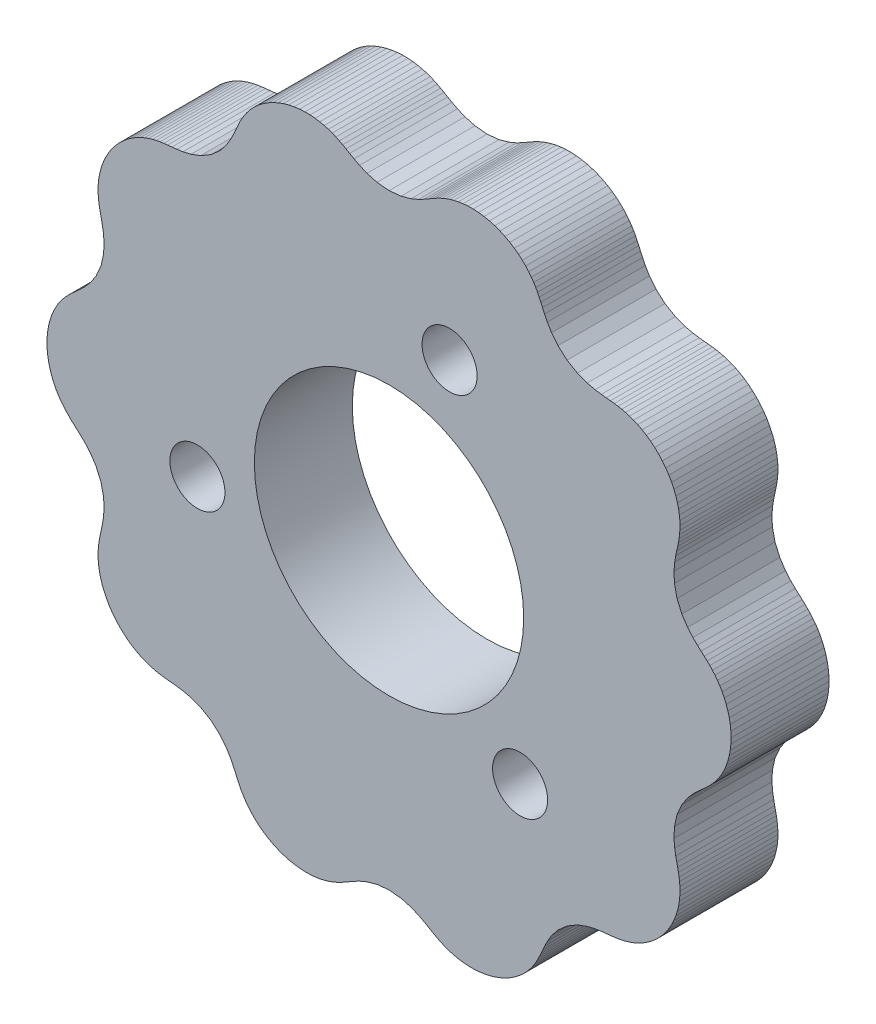
SolidWorks part; units mm, degrees
ref_plane "Front Plane" through (0, 0, 0) normal (0, 0, 1) x (1, 0, 0)
ref_plane "Top Plane" through (0, 0, 0) normal (0, 1, 0) x (1, 0, 0)
ref_plane "Right Plane" through (0, 0, 0) normal (1, 0, 0) x (0, 0, -1)
sketch "Model" plane through (0, 0, 0) normal (0, 0, 1) x (1, 0, 0)
  line L0 (20.955, 0) -> (20.9416, 0.365) construction
  line L1 (20.9416, 0.365) -> (20.9019, 0.7253) construction
  line L2 (20.9019, 0.7253) -> (20.8371, 1.0767) construction
  line L3 (20.8371, 1.0767) -> (20.749, 1.4151) construction
  line L4 (20.749, 1.4151) -> (20.6403, 1.7368) construction
  line L5 (20.6403, 1.7368) -> (20.514, 2.0391) construction
  line L6 (20.514, 2.0391) -> (20.3735, 2.32) construction
  line L7 (20.3735, 2.32) -> (20.2221, 2.5783) construction
  line L8 (20.2221, 2.5783) -> (20.0631, 2.8139) construction
  line L9 (20.0631, 2.8139) -> (19.8992, 3.0281) construction
  line L10 (19.8992, 3.0281) -> (19.7321, 3.2232) construction
  line L11 (19.7321, 3.2232) -> (19.5618, 3.4033) construction
  line L12 (19.5618, 3.4033) -> (19.3864, 3.5744) construction
  line L13 (19.3864, 3.5744) -> (19.2007, 3.7451) construction
  line L14 (19.2007, 3.7451) -> (18.9953, 3.9287) construction
  line L15 (18.9953, 3.9287) -> (18.7567, 4.1455) construction
  line L16 (18.7567, 4.1455) -> (18.4694, 4.4274) construction
  line L17 (18.4694, 4.4274) -> (18.1274, 4.8212) construction
  line L18 (18.1274, 4.8212) -> (17.7602, 5.3749) construction
  line L19 (17.7602, 5.3749) -> (17.4515, 6.083) construction
  line L20 (17.4515, 6.083) -> (17.285, 6.8373) construction
  line L21 (17.285, 6.8373) -> (17.2567, 7.5011) construction
  line L22 (17.2567, 7.5011) -> (17.3019, 8.0207) construction
  line L23 (17.3019, 8.0207) -> (17.3686, 8.4177) construction
  line L24 (17.3686, 8.4177) -> (17.4342, 8.7332) construction
  line L25 (17.4342, 8.7332) -> (17.4925, 9.0025) construction
  line L26 (17.4925, 9.0025) -> (17.5424, 9.2498) construction
  line L27 (17.5424, 9.2498) -> (17.5837, 9.4913) construction
  line L28 (17.5837, 9.4913) -> (17.6156, 9.7371) construction
  line L29 (17.6156, 9.7371) -> (17.6361, 9.9932) construction
  line L30 (17.6361, 9.9932) -> (17.6428, 10.2628) construction
  line L31 (17.6428, 10.2628) -> (17.6329, 10.5469) construction
  line L32 (17.6329, 10.5469) -> (17.6036, 10.8448) construction
  line L33 (17.6036, 10.8448) -> (17.5522, 11.1546) construction
  line L34 (17.5522, 11.1546) -> (17.4767, 11.4734) construction
  line L35 (17.4767, 11.4734) -> (17.3755, 11.7977) construction
  line L36 (17.3755, 11.7977) -> (17.2479, 12.1231) construction
  line L37 (17.2479, 12.1231) -> (17.0938, 12.4455) construction
  line L38 (17.0938, 12.4455) -> (16.9141, 12.7604) construction
  line L39 (16.9141, 12.7604) -> (16.7104, 13.0635) construction
  line L40 (16.7104, 13.0635) -> (16.4851, 13.3509) construction
  line L41 (16.4851, 13.3509) -> (16.2411, 13.6191) construction
  line L42 (16.2411, 13.6191) -> (15.9821, 13.8653) construction
  line L43 (15.9821, 13.8653) -> (15.712, 14.0873) construction
  line L44 (15.712, 14.0873) -> (15.4349, 14.2837) construction
  line L45 (15.4349, 14.2837) -> (15.1551, 14.454) construction
  line L46 (15.1551, 14.454) -> (14.8763, 14.5986) construction
  line L47 (14.8763, 14.5986) -> (14.602, 14.7186) construction
  line L48 (14.602, 14.7186) -> (14.3349, 14.8158) construction
  line L49 (14.3349, 14.8158) -> (14.0764, 14.8927) construction
  line L50 (14.0764, 14.8927) -> (13.8265, 14.9523) construction
  line L51 (13.8265, 14.9523) -> (13.5829, 14.998) construction
  line L52 (13.5829, 14.998) -> (13.3405, 15.0333) construction
  line L53 (13.3405, 15.0333) -> (13.0898, 15.0622) construction
  line L54 (13.0898, 15.0622) -> (12.8157, 15.0901) construction
  line L55 (12.8157, 15.0901) -> (12.4953, 15.1252) construction
  line L56 (12.4953, 15.1252) -> (12.0972, 15.1844) construction
  line L57 (12.0972, 15.1844) -> (11.589, 15.302) construction
  line L58 (11.589, 15.302) -> (10.9665, 15.534) construction
  line L59 (10.9665, 15.534) -> (10.3006, 15.9255) construction
  line L60 (10.3006, 15.9255) -> (9.7225, 16.4379) construction
  line L61 (9.7225, 16.4379) -> (9.3094, 16.9582) construction
  line L62 (9.3094, 16.9582) -> (9.0405, 17.4052) construction
  line L63 (9.0405, 17.4052) -> (8.8612, 17.7655) construction
  line L64 (8.8612, 17.7655) -> (8.7288, 18.0594) construction
  line L65 (8.7288, 18.0594) -> (8.6176, 18.3115) construction
  line L66 (8.6176, 18.3115) -> (8.5126, 18.5409) construction
  line L67 (8.5126, 18.5409) -> (8.4041, 18.7606) construction
  line L68 (8.4041, 18.7606) -> (8.2854, 18.9781) construction
  line L69 (8.2854, 18.9781) -> (8.1515, 19.1974) construction
  line L70 (8.1515, 19.1974) -> (7.9985, 19.4194) construction
  line L71 (7.9985, 19.4194) -> (7.8235, 19.6434) construction
  line L72 (7.8235, 19.6434) -> (7.6246, 19.8672) construction
  line L73 (7.6246, 19.8672) -> (7.401, 20.0877) construction
  line L74 (7.401, 20.0877) -> (7.1525, 20.3012) construction
  line L75 (7.1525, 20.3012) -> (6.8801, 20.5041) construction
  line L76 (6.8801, 20.5041) -> (6.5855, 20.6924) construction
  line L77 (6.5855, 20.6924) -> (6.2713, 20.8626) construction
  line L78 (6.2713, 20.8626) -> (5.9409, 21.0117) construction
  line L79 (5.9409, 21.0117) -> (5.5979, 21.1372) construction
  line L80 (5.5979, 21.1372) -> (5.2467, 21.2373) construction
  line L81 (5.2467, 21.2373) -> (4.8917, 21.3109) construction
  line L82 (4.8917, 21.3109) -> (4.5374, 21.3578) construction
  line L83 (4.5374, 21.3578) -> (4.1885, 21.3786) construction
  line L84 (4.1885, 21.3786) -> (3.8489, 21.3747) construction
  line L85 (3.8489, 21.3747) -> (3.5223, 21.348) construction
  line L86 (3.5223, 21.348) -> (3.2118, 21.3011) construction
  line L87 (3.2118, 21.3011) -> (2.9193, 21.2369) construction
  line L88 (2.9193, 21.2369) -> (2.6461, 21.1585) construction
  line L89 (2.6461, 21.1585) -> (2.3918, 21.0688) construction
  line L90 (2.3918, 21.0688) -> (2.1545, 20.9702) construction
  line L91 (2.1545, 20.9702) -> (1.9307, 20.8639) construction
  line L92 (1.9307, 20.8639) -> (1.7138, 20.75) construction
  line L93 (1.7138, 20.75) -> (1.4939, 20.6261) construction
  line L94 (1.4939, 20.6261) -> (1.2559, 20.4875) construction
  line L95 (1.2559, 20.4875) -> (0.976, 20.3276) construction
  line L96 (0.976, 20.3276) -> (0.6191, 20.1415) construction
  line L97 (0.6191, 20.1415) -> (0.1389, 19.9379) construction
  line L98 (0.1389, 19.9379) -> (-0.5012, 19.7597) construction
  line L99 (-0.5012, 19.7597) -> (-1.27, 19.685) construction
  line L100 (-1.27, 19.685) -> (-2.0388, 19.7597) construction
  line L101 (-2.0388, 19.7597) -> (-2.6789, 19.9379) construction
  line L102 (-2.6789, 19.9379) -> (-3.1591, 20.1415) construction
  line L103 (-3.1591, 20.1415) -> (-3.516, 20.3276) construction
  line L104 (-3.516, 20.3276) -> (-3.7959, 20.4875) construction
  line L105 (-3.7959, 20.4875) -> (-4.0339, 20.6261) construction
  line L106 (-4.0339, 20.6261) -> (-4.2538, 20.75) construction
  line L107 (-4.2538, 20.75) -> (-4.4707, 20.8639) construction
  line L108 (-4.4707, 20.8639) -> (-4.6945, 20.9702) construction
  line L109 (-4.6945, 20.9702) -> (-4.9318, 21.0688) construction
  line L110 (-4.9318, 21.0688) -> (-5.1861, 21.1585) construction
  line L111 (-5.1861, 21.1585) -> (-5.4593, 21.2369) construction
  line L112 (-5.4593, 21.2369) -> (-5.7518, 21.3011) construction
  line L113 (-5.7518, 21.3011) -> (-6.0623, 21.348) construction
  line L114 (-6.0623, 21.348) -> (-6.3889, 21.3747) construction
  line L115 (-6.3889, 21.3747) -> (-6.7285, 21.3786) construction
  line L116 (-6.7285, 21.3786) -> (-7.0774, 21.3578) construction
  line L117 (-7.0774, 21.3578) -> (-7.4317, 21.3109) construction
  line L118 (-7.4317, 21.3109) -> (-7.7867, 21.2373) construction
  line L119 (-7.7867, 21.2373) -> (-8.1379, 21.1372) construction
  line L120 (-8.1379, 21.1372) -> (-8.4809, 21.0117) construction
  line L121 (-8.4809, 21.0117) -> (-8.8113, 20.8626) construction
  line L122 (-8.8113, 20.8626) -> (-9.1255, 20.6924) construction
  line L123 (-9.1255, 20.6924) -> (-9.4201, 20.5041) construction
  line L124 (-9.4201, 20.5041) -> (-9.6925, 20.3012) construction
  line L125 (-9.6925, 20.3012) -> (-9.941, 20.0877) construction
  line L126 (-9.941, 20.0877) -> (-10.1646, 19.8672) construction
  line L127 (-10.1646, 19.8672) -> (-10.3635, 19.6434) construction
  line L128 (-10.3635, 19.6434) -> (-10.5385, 19.4194) construction
  line L129 (-10.5385, 19.4194) -> (-10.6915, 19.1974) construction
  line L130 (-10.6915, 19.1974) -> (-10.8254, 18.9781) construction
  line L131 (-10.8254, 18.9781) -> (-10.9441, 18.7606) construction
  line L132 (-10.9441, 18.7606) -> (-11.0526, 18.5409) construction
  line L133 (-11.0526, 18.5409) -> (-11.1576, 18.3115) construction
  line L134 (-11.1576, 18.3115) -> (-11.2688, 18.0594) construction
  line L135 (-11.2688, 18.0594) -> (-11.4012, 17.7655) construction
  line L136 (-11.4012, 17.7655) -> (-11.5805, 17.4052) construction
  line L137 (-11.5805, 17.4052) -> (-11.8494, 16.9582) construction
  line L138 (-11.8494, 16.9582) -> (-12.2625, 16.4379) construction
  line L139 (-12.2625, 16.4379) -> (-12.8406, 15.9255) construction
  line L140 (-12.8406, 15.9255) -> (-13.5065, 15.534) construction
  line L141 (-13.5065, 15.534) -> (-14.129, 15.302) construction
  line L142 (-14.129, 15.302) -> (-14.6372, 15.1844) construction
  line L143 (-14.6372, 15.1844) -> (-15.0353, 15.1252) construction
  line L144 (-15.0353, 15.1252) -> (-15.3557, 15.0901) construction
  line L145 (-15.3557, 15.0901) -> (-15.6298, 15.0622) construction
  line L146 (-15.6298, 15.0622) -> (-15.8805, 15.0333) construction
  line L147 (-15.8805, 15.0333) -> (-16.1229, 14.998) construction
  line L148 (-16.1229, 14.998) -> (-16.3665, 14.9523) construction
  line L149 (-16.3665, 14.9523) -> (-16.6164, 14.8927) construction
  line L150 (-16.6164, 14.8927) -> (-16.8749, 14.8158) construction
  line L151 (-16.8749, 14.8158) -> (-17.142, 14.7186) construction
  line L152 (-17.142, 14.7186) -> (-17.4163, 14.5986) construction
  line L153 (-17.4163, 14.5986) -> (-17.6951, 14.454) construction
  line L154 (-17.6951, 14.454) -> (-17.9749, 14.2837) construction
  line L155 (-17.9749, 14.2837) -> (-18.252, 14.0873) construction
  line L156 (-18.252, 14.0873) -> (-18.5221, 13.8653) construction
  line L157 (-18.5221, 13.8653) -> (-18.7811, 13.6191) construction
  line L158 (-18.7811, 13.6191) -> (-19.0251, 13.3509) construction
  line L159 (-19.0251, 13.3509) -> (-19.2504, 13.0635) construction
  line L160 (-19.2504, 13.0635) -> (-19.4541, 12.7604) construction
  line L161 (-19.4541, 12.7604) -> (-19.6338, 12.4455) construction
  line L162 (-19.6338, 12.4455) -> (-19.7879, 12.1231) construction
  line L163 (-19.7879, 12.1231) -> (-19.9155, 11.7977) construction
  line L164 (-19.9155, 11.7977) -> (-20.0167, 11.4734) construction
  line L165 (-20.0167, 11.4734) -> (-20.0922, 11.1546) construction
  line L166 (-20.0922, 11.1546) -> (-20.1436, 10.8448) construction
  line L167 (-20.1436, 10.8448) -> (-20.1729, 10.5469) construction
  line L168 (-20.1729, 10.5469) -> (-20.1828, 10.2628) construction
  line L169 (-20.1828, 10.2628) -> (-20.1761, 9.9932) construction
  line L170 (-20.1761, 9.9932) -> (-20.1556, 9.7371) construction
  line L171 (-20.1556, 9.7371) -> (-20.1237, 9.4913) construction
  line L172 (-20.1237, 9.4913) -> (-20.0824, 9.2498) construction
  line L173 (-20.0824, 9.2498) -> (-20.0325, 9.0025) construction
  line L174 (-20.0325, 9.0025) -> (-19.9742, 8.7332) construction
  line L175 (-19.9742, 8.7332) -> (-19.9086, 8.4177) construction
  line L176 (-19.9086, 8.4177) -> (-19.8419, 8.0207) construction
  line L177 (-19.8419, 8.0207) -> (-19.7967, 7.5011) construction
  line L178 (-19.7967, 7.5011) -> (-19.825, 6.8373) construction
  line L179 (-19.825, 6.8373) -> (-19.9915, 6.083) construction
  line L180 (-19.9915, 6.083) -> (-20.3002, 5.3749) construction
  line L181 (-20.3002, 5.3749) -> (-20.6674, 4.8212) construction
  line L182 (-20.6674, 4.8212) -> (-21.0094, 4.4274) construction
  line L183 (-21.0094, 4.4274) -> (-21.2967, 4.1455) construction
  line L184 (-21.2967, 4.1455) -> (-21.5353, 3.9287) construction
  line L185 (-21.5353, 3.9287) -> (-21.7407, 3.7451) construction
  line L186 (-21.7407, 3.7451) -> (-21.9264, 3.5744) construction
  line L187 (-21.9264, 3.5744) -> (-22.1018, 3.4033) construction
  line L188 (-22.1018, 3.4033) -> (-22.2721, 3.2232) construction
  line L189 (-22.2721, 3.2232) -> (-22.4392, 3.0281) construction
  line L190 (-22.4392, 3.0281) -> (-22.6031, 2.8139) construction
  line L191 (-22.6031, 2.8139) -> (-22.7621, 2.5783) construction
  line L192 (-22.7621, 2.5783) -> (-22.9135, 2.32) construction
  line L193 (-22.9135, 2.32) -> (-23.054, 2.0391) construction
  line L194 (-23.054, 2.0391) -> (-23.1803, 1.7368) construction
  line L195 (-23.1803, 1.7368) -> (-23.289, 1.4151) construction
  line L196 (-23.289, 1.4151) -> (-23.3771, 1.0767) construction
  line L197 (-23.3771, 1.0767) -> (-23.4419, 0.7253) construction
  line L198 (-23.4419, 0.7253) -> (-23.4816, 0.365) construction
  line L199 (-23.4816, 0.365) -> (-23.495, 0) construction
  line L200 (-23.495, 0) -> (-23.4816, -0.365) construction
  line L201 (-23.4816, -0.365) -> (-23.4419, -0.7253) construction
  line L202 (-23.4419, -0.7253) -> (-23.3771, -1.0767) construction
  line L203 (-23.3771, -1.0767) -> (-23.289, -1.4151) construction
  line L204 (-23.289, -1.4151) -> (-23.1803, -1.7368) construction
  line L205 (-23.1803, -1.7368) -> (-23.054, -2.0391) construction
  line L206 (-23.054, -2.0391) -> (-22.9135, -2.32) construction
  line L207 (-22.9135, -2.32) -> (-22.7621, -2.5783) construction
  line L208 (-22.7621, -2.5783) -> (-22.6031, -2.8139) construction
  line L209 (-22.6031, -2.8139) -> (-22.4392, -3.0281) construction
  line L210 (-22.4392, -3.0281) -> (-22.2721, -3.2232) construction
  line L211 (-22.2721, -3.2232) -> (-22.1018, -3.4033) construction
  line L212 (-22.1018, -3.4033) -> (-21.9264, -3.5744) construction
  line L213 (-21.9264, -3.5744) -> (-21.7407, -3.7451) construction
  line L214 (-21.7407, -3.7451) -> (-21.5353, -3.9287) construction
  line L215 (-21.5353, -3.9287) -> (-21.2967, -4.1455) construction
  line L216 (-21.2967, -4.1455) -> (-21.0094, -4.4274) construction
  line L217 (-21.0094, -4.4274) -> (-20.6674, -4.8212) construction
  line L218 (-20.6674, -4.8212) -> (-20.3002, -5.3749) construction
  line L219 (-20.3002, -5.3749) -> (-19.9915, -6.083) construction
  line L220 (-19.9915, -6.083) -> (-19.825, -6.8373) construction
  line L221 (-19.825, -6.8373) -> (-19.7967, -7.5011) construction
  line L222 (-19.7967, -7.5011) -> (-19.8419, -8.0207) construction
  line L223 (-19.8419, -8.0207) -> (-19.9086, -8.4177) construction
  line L224 (-19.9086, -8.4177) -> (-19.9742, -8.7332) construction
  line L225 (-19.9742, -8.7332) -> (-20.0325, -9.0025) construction
  line L226 (-20.0325, -9.0025) -> (-20.0824, -9.2498) construction
  line L227 (-20.0824, -9.2498) -> (-20.1237, -9.4913) construction
  line L228 (-20.1237, -9.4913) -> (-20.1556, -9.7371) construction
  line L229 (-20.1556, -9.7371) -> (-20.1761, -9.9932) construction
  line L230 (-20.1761, -9.9932) -> (-20.1828, -10.2628) construction
  line L231 (-20.1828, -10.2628) -> (-20.1729, -10.5469) construction
  line L232 (-20.1729, -10.5469) -> (-20.1436, -10.8448) construction
  line L233 (-20.1436, -10.8448) -> (-20.0922, -11.1546) construction
  line L234 (-20.0922, -11.1546) -> (-20.0167, -11.4734) construction
  line L235 (-20.0167, -11.4734) -> (-19.9155, -11.7977) construction
  line L236 (-19.9155, -11.7977) -> (-19.7879, -12.1231) construction
  line L237 (-19.7879, -12.1231) -> (-19.6338, -12.4455) construction
  line L238 (-19.6338, -12.4455) -> (-19.4541, -12.7604) construction
  line L239 (-19.4541, -12.7604) -> (-19.2504, -13.0635) construction
  line L240 (-19.2504, -13.0635) -> (-19.0251, -13.3509) construction
  line L241 (-19.0251, -13.3509) -> (-18.7811, -13.6191) construction
  line L242 (-18.7811, -13.6191) -> (-18.5221, -13.8653) construction
  line L243 (-18.5221, -13.8653) -> (-18.252, -14.0873) construction
  line L244 (-18.252, -14.0873) -> (-17.9749, -14.2837) construction
  line L245 (-17.9749, -14.2837) -> (-17.6951, -14.454) construction
  line L246 (-17.6951, -14.454) -> (-17.4163, -14.5986) construction
  line L247 (-17.4163, -14.5986) -> (-17.142, -14.7186) construction
  line L248 (-17.142, -14.7186) -> (-16.8749, -14.8158) construction
  line L249 (-16.8749, -14.8158) -> (-16.6164, -14.8927) construction
  line L250 (-16.6164, -14.8927) -> (-16.3665, -14.9523) construction
  line L251 (-16.3665, -14.9523) -> (-16.1229, -14.998) construction
  line L252 (-16.1229, -14.998) -> (-15.8805, -15.0333) construction
  line L253 (-15.8805, -15.0333) -> (-15.6298, -15.0622) construction
  line L254 (-15.6298, -15.0622) -> (-15.3557, -15.0901) construction
  line L255 (-15.3557, -15.0901) -> (-15.0353, -15.1252) construction
  line L256 (-15.0353, -15.1252) -> (-14.6372, -15.1844) construction
  line L257 (-14.6372, -15.1844) -> (-14.129, -15.302) construction
  line L258 (-14.129, -15.302) -> (-13.5065, -15.534) construction
  line L259 (-13.5065, -15.534) -> (-12.8406, -15.9255) construction
  line L260 (-12.8406, -15.9255) -> (-12.2625, -16.4379) construction
  line L261 (-12.2625, -16.4379) -> (-11.8494, -16.9582) construction
  line L262 (-11.8494, -16.9582) -> (-11.5805, -17.4052) construction
  line L263 (-11.5805, -17.4052) -> (-11.4012, -17.7655) construction
  line L264 (-11.4012, -17.7655) -> (-11.2688, -18.0594) construction
  line L265 (-11.2688, -18.0594) -> (-11.1576, -18.3115) construction
  line L266 (-11.1576, -18.3115) -> (-11.0526, -18.5409) construction
  line L267 (-11.0526, -18.5409) -> (-10.9441, -18.7606) construction
  line L268 (-10.9441, -18.7606) -> (-10.8254, -18.9781) construction
  line L269 (-10.8254, -18.9781) -> (-10.6915, -19.1974) construction
  line L270 (-10.6915, -19.1974) -> (-10.5385, -19.4194) construction
  line L271 (-10.5385, -19.4194) -> (-10.3635, -19.6434) construction
  line L272 (-10.3635, -19.6434) -> (-10.1646, -19.8672) construction
  line L273 (-10.1646, -19.8672) -> (-9.941, -20.0877) construction
  line L274 (-9.941, -20.0877) -> (-9.6925, -20.3012) construction
  line L275 (-9.6925, -20.3012) -> (-9.4201, -20.5041) construction
  line L276 (-9.4201, -20.5041) -> (-9.1255, -20.6924) construction
  line L277 (-9.1255, -20.6924) -> (-8.8113, -20.8626) construction
  line L278 (-8.8113, -20.8626) -> (-8.4809, -21.0117) construction
  line L279 (-8.4809, -21.0117) -> (-8.1379, -21.1372) construction
  line L280 (-8.1379, -21.1372) -> (-7.7867, -21.2373) construction
  line L281 (-7.7867, -21.2373) -> (-7.4317, -21.3109) construction
  line L282 (-7.4317, -21.3109) -> (-7.0774, -21.3578) construction
  line L283 (-7.0774, -21.3578) -> (-6.7285, -21.3786) construction
  line L284 (-6.7285, -21.3786) -> (-6.3889, -21.3747) construction
  line L285 (-6.3889, -21.3747) -> (-6.0623, -21.348) construction
  line L286 (-6.0623, -21.348) -> (-5.7518, -21.3011) construction
  line L287 (-5.7518, -21.3011) -> (-5.4593, -21.2369) construction
  line L288 (-5.4593, -21.2369) -> (-5.1861, -21.1585) construction
  line L289 (-5.1861, -21.1585) -> (-4.9318, -21.0688) construction
  line L290 (-4.9318, -21.0688) -> (-4.6945, -20.9702) construction
  line L291 (-4.6945, -20.9702) -> (-4.4707, -20.8639) construction
  line L292 (-4.4707, -20.8639) -> (-4.2538, -20.75) construction
  line L293 (-4.2538, -20.75) -> (-4.0339, -20.6261) construction
  line L294 (-4.0339, -20.6261) -> (-3.7959, -20.4875) construction
  line L295 (-3.7959, -20.4875) -> (-3.516, -20.3276) construction
  line L296 (-3.516, -20.3276) -> (-3.1591, -20.1415) construction
  line L297 (-3.1591, -20.1415) -> (-2.6789, -19.9379) construction
  line L298 (-2.6789, -19.9379) -> (-2.0388, -19.7597) construction
  line L299 (-2.0388, -19.7597) -> (-1.27, -19.685) construction
  line L300 (-1.27, -19.685) -> (-0.5012, -19.7597) construction
  line L301 (-0.5012, -19.7597) -> (0.1389, -19.9379) construction
  line L302 (0.1389, -19.9379) -> (0.6191, -20.1415) construction
  line L303 (0.6191, -20.1415) -> (0.976, -20.3276) construction
  line L304 (0.976, -20.3276) -> (1.2559, -20.4875) construction
  line L305 (1.2559, -20.4875) -> (1.4939, -20.6261) construction
  line L306 (1.4939, -20.6261) -> (1.7138, -20.75) construction
  line L307 (1.7138, -20.75) -> (1.9307, -20.8639) construction
  line L308 (1.9307, -20.8639) -> (2.1545, -20.9702) construction
  line L309 (2.1545, -20.9702) -> (2.3918, -21.0688) construction
  line L310 (2.3918, -21.0688) -> (2.6461, -21.1585) construction
  line L311 (2.6461, -21.1585) -> (2.9193, -21.2369) construction
  line L312 (2.9193, -21.2369) -> (3.2118, -21.3011) construction
  line L313 (3.2118, -21.3011) -> (3.5223, -21.348) construction
  line L314 (3.5223, -21.348) -> (3.8489, -21.3747) construction
  line L315 (3.8489, -21.3747) -> (4.1885, -21.3786) construction
  line L316 (4.1885, -21.3786) -> (4.5374, -21.3578) construction
  line L317 (4.5374, -21.3578) -> (4.8917, -21.3109) construction
  line L318 (4.8917, -21.3109) -> (5.2467, -21.2373) construction
  line L319 (5.2467, -21.2373) -> (5.5979, -21.1372) construction
  line L320 (5.5979, -21.1372) -> (5.9409, -21.0117) construction
  line L321 (5.9409, -21.0117) -> (6.2713, -20.8626) construction
  line L322 (6.2713, -20.8626) -> (6.5855, -20.6924) construction
  line L323 (6.5855, -20.6924) -> (6.8801, -20.5041) construction
  line L324 (6.8801, -20.5041) -> (7.1525, -20.3012) construction
  line L325 (7.1525, -20.3012) -> (7.401, -20.0877) construction
  line L326 (7.401, -20.0877) -> (7.6246, -19.8672) construction
  line L327 (7.6246, -19.8672) -> (7.8235, -19.6434) construction
  line L328 (7.8235, -19.6434) -> (7.9985, -19.4194) construction
  line L329 (7.9985, -19.4194) -> (8.1515, -19.1974) construction
  line L330 (8.1515, -19.1974) -> (8.2854, -18.9781) construction
  line L331 (8.2854, -18.9781) -> (8.4041, -18.7606) construction
  line L332 (8.4041, -18.7606) -> (8.5126, -18.5409) construction
  line L333 (8.5126, -18.5409) -> (8.6176, -18.3115) construction
  line L334 (8.6176, -18.3115) -> (8.7288, -18.0594) construction
  line L335 (8.7288, -18.0594) -> (8.8612, -17.7655) construction
  line L336 (8.8612, -17.7655) -> (9.0405, -17.4052) construction
  line L337 (9.0405, -17.4052) -> (9.3094, -16.9582) construction
  line L338 (9.3094, -16.9582) -> (9.7225, -16.4379) construction
  line L339 (9.7225, -16.4379) -> (10.3006, -15.9255) construction
  line L340 (10.3006, -15.9255) -> (10.9665, -15.534) construction
  line L341 (10.9665, -15.534) -> (11.589, -15.302) construction
  line L342 (11.589, -15.302) -> (12.0972, -15.1844) construction
  line L343 (12.0972, -15.1844) -> (12.4953, -15.1252) construction
  line L344 (12.4953, -15.1252) -> (12.8157, -15.0901) construction
  line L345 (12.8157, -15.0901) -> (13.0898, -15.0622) construction
  line L346 (13.0898, -15.0622) -> (13.3405, -15.0333) construction
  line L347 (13.3405, -15.0333) -> (13.5829, -14.998) construction
  line L348 (13.5829, -14.998) -> (13.8265, -14.9523) construction
  line L349 (13.8265, -14.9523) -> (14.0764, -14.8927) construction
  line L350 (14.0764, -14.8927) -> (14.3349, -14.8158) construction
  line L351 (14.3349, -14.8158) -> (14.602, -14.7186) construction
  line L352 (14.602, -14.7186) -> (14.8763, -14.5986) construction
  line L353 (14.8763, -14.5986) -> (15.1551, -14.454) construction
  line L354 (15.1551, -14.454) -> (15.4349, -14.2837) construction
  line L355 (15.4349, -14.2837) -> (15.712, -14.0873) construction
  line L356 (15.712, -14.0873) -> (15.9821, -13.8653) construction
  line L357 (15.9821, -13.8653) -> (16.2411, -13.6191) construction
  line L358 (16.2411, -13.6191) -> (16.4851, -13.3509) construction
  line L359 (16.4851, -13.3509) -> (16.7104, -13.0635) construction
  line L360 (16.7104, -13.0635) -> (16.9141, -12.7604) construction
  line L361 (16.9141, -12.7604) -> (17.0938, -12.4455) construction
  line L362 (17.0938, -12.4455) -> (17.2479, -12.1231) construction
  line L363 (17.2479, -12.1231) -> (17.3755, -11.7977) construction
  line L364 (17.3755, -11.7977) -> (17.4767, -11.4734) construction
  line L365 (17.4767, -11.4734) -> (17.5522, -11.1546) construction
  line L366 (17.5522, -11.1546) -> (17.6036, -10.8448) construction
  line L367 (17.6036, -10.8448) -> (17.6329, -10.5469) construction
  line L368 (17.6329, -10.5469) -> (17.6428, -10.2628) construction
  line L369 (17.6428, -10.2628) -> (17.6361, -9.9932) construction
  line L370 (17.6361, -9.9932) -> (17.6156, -9.7371) construction
  line L371 (17.6156, -9.7371) -> (17.5837, -9.4913) construction
  line L372 (17.5837, -9.4913) -> (17.5424, -9.2498) construction
  line L373 (17.5424, -9.2498) -> (17.4925, -9.0025) construction
  line L374 (17.4925, -9.0025) -> (17.4342, -8.7332) construction
  line L375 (17.4342, -8.7332) -> (17.3686, -8.4177) construction
  line L376 (17.3686, -8.4177) -> (17.3019, -8.0207) construction
  line L377 (17.3019, -8.0207) -> (17.2567, -7.5011) construction
  line L378 (17.2567, -7.5011) -> (17.285, -6.8373) construction
  line L379 (17.285, -6.8373) -> (17.4515, -6.083) construction
  line L380 (17.4515, -6.083) -> (17.7602, -5.3749) construction
  line L381 (17.7602, -5.3749) -> (18.1274, -4.8212) construction
  line L382 (18.1274, -4.8212) -> (18.4694, -4.4274) construction
  line L383 (18.4694, -4.4274) -> (18.7567, -4.1455) construction
  line L384 (18.7567, -4.1455) -> (18.9953, -3.9287) construction
  line L385 (18.9953, -3.9287) -> (19.2007, -3.7451) construction
  line L386 (19.2007, -3.7451) -> (19.3864, -3.5744) construction
  line L387 (19.3864, -3.5744) -> (19.5618, -3.4033) construction
  line L388 (19.5618, -3.4033) -> (19.7321, -3.2232) construction
  line L389 (19.7321, -3.2232) -> (19.8992, -3.0281) construction
  line L390 (19.8992, -3.0281) -> (20.0631, -2.8139) construction
  line L391 (20.0631, -2.8139) -> (20.2221, -2.5783) construction
  line L392 (20.2221, -2.5783) -> (20.3735, -2.32) construction
  line L393 (20.3735, -2.32) -> (20.514, -2.0391) construction
  line L394 (20.514, -2.0391) -> (20.6403, -1.7368) construction
  line L395 (20.6403, -1.7368) -> (20.749, -1.4151) construction
  line L396 (20.749, -1.4151) -> (20.8371, -1.0767) construction
  line L397 (20.8371, -1.0767) -> (20.9019, -0.7253) construction
  line L398 (20.9019, -0.7253) -> (20.9416, -0.365) construction
  line L399 (20.9416, -0.365) -> (20.955, 0) construction
  line L400 (20.9042, 0) -> (20.8909, 0.3612)
  line L401 (20.8909, 0.3612) -> (20.8516, 0.7179)
  line L402 (20.8516, 0.7179) -> (20.7875, 1.0657)
  line L403 (20.7875, 1.0657) -> (20.7003, 1.4005)
  line L404 (20.7003, 1.4005) -> (20.5928, 1.7189)
  line L405 (20.5928, 1.7189) -> (20.4678, 2.018)
  line L406 (20.4678, 2.018) -> (20.3288, 2.2958)
  line L407 (20.3288, 2.2958) -> (20.1791, 2.5512)
  line L408 (20.1791, 2.5512) -> (20.0218, 2.7843)
  line L409 (20.0218, 2.7843) -> (19.8597, 2.9961)
  line L410 (19.8597, 2.9961) -> (19.6943, 3.1892)
  line L411 (19.6943, 3.1892) -> (19.5256, 3.3677)
  line L412 (19.5256, 3.3677) -> (19.3515, 3.5375)
  line L413 (19.3515, 3.5375) -> (19.1666, 3.7075)
  line L414 (19.1666, 3.7075) -> (18.9613, 3.891)
  line L415 (18.9613, 3.891) -> (18.7218, 4.1085)
  line L416 (18.7218, 4.1085) -> (18.4324, 4.3925)
  line L417 (18.4324, 4.3925) -> (18.0869, 4.7904)
  line L418 (18.0869, 4.7904) -> (17.7154, 5.3505)
  line L419 (17.7154, 5.3505) -> (17.403, 6.0672)
  line L420 (17.403, 6.0672) -> (17.2345, 6.8307)
  line L421 (17.2345, 6.8307) -> (17.2058, 7.5022)
  line L422 (17.2058, 7.5022) -> (17.2515, 8.0271)
  line L423 (17.2515, 8.0271) -> (17.3187, 8.427)
  line L424 (17.3187, 8.427) -> (17.3845, 8.7438)
  line L425 (17.3845, 8.7438) -> (17.4427, 9.0129)
  line L426 (17.4427, 9.0129) -> (17.4924, 9.2591)
  line L427 (17.4924, 9.2591) -> (17.5335, 9.4989)
  line L428 (17.5335, 9.4989) -> (17.565, 9.7424)
  line L429 (17.565, 9.7424) -> (17.5854, 9.9958)
  line L430 (17.5854, 9.9958) -> (17.592, 10.2625)
  line L431 (17.592, 10.2625) -> (17.5822, 10.5435)
  line L432 (17.5822, 10.5435) -> (17.5532, 10.8381)
  line L433 (17.5532, 10.8381) -> (17.5024, 11.1446)
  line L434 (17.5024, 11.1446) -> (17.4277, 11.46)
  line L435 (17.4277, 11.46) -> (17.3276, 11.7808)
  line L436 (17.3276, 11.7808) -> (17.2013, 12.1029)
  line L437 (17.2013, 12.1029) -> (17.0488, 12.4219)
  line L438 (17.0488, 12.4219) -> (16.8709, 12.7336)
  line L439 (16.8709, 12.7336) -> (16.6693, 13.0336)
  line L440 (16.6693, 13.0336) -> (16.4462, 13.3181)
  line L441 (16.4462, 13.3181) -> (16.2048, 13.5836)
  line L442 (16.2048, 13.5836) -> (15.9485, 13.8272)
  line L443 (15.9485, 13.8272) -> (15.6812, 14.0469)
  line L444 (15.6812, 14.0469) -> (15.407, 14.2412)
  line L445 (15.407, 14.2412) -> (15.1301, 14.4097)
  line L446 (15.1301, 14.4097) -> (14.8544, 14.5527)
  line L447 (14.8544, 14.5527) -> (14.5831, 14.6714)
  line L448 (14.5831, 14.6714) -> (14.3189, 14.7675)
  line L449 (14.3189, 14.7675) -> (14.0632, 14.8436)
  line L450 (14.0632, 14.8436) -> (13.8159, 14.9026)
  line L451 (13.8159, 14.9026) -> (13.5746, 14.9479)
  line L452 (13.5746, 14.9479) -> (13.3339, 14.9829)
  line L453 (13.3339, 14.9829) -> (13.0843, 15.0117)
  line L454 (13.0843, 15.0117) -> (12.8104, 15.0395)
  line L455 (12.8104, 15.0395) -> (12.4888, 15.0748)
  line L456 (12.4888, 15.0748) -> (12.0877, 15.1344)
  line L457 (12.0877, 15.1344) -> (11.5743, 15.2533)
  line L458 (11.5743, 15.2533) -> (10.9446, 15.488)
  line L459 (10.9446, 15.488) -> (10.2706, 15.8842)
  line L460 (10.2706, 15.8842) -> (9.6855, 16.4028)
  line L461 (9.6855, 16.4028) -> (9.2676, 16.9292)
  line L462 (9.2676, 16.9292) -> (8.9959, 17.3807)
  line L463 (8.9959, 17.3807) -> (8.8152, 17.7438)
  line L464 (8.8152, 17.7438) -> (8.6824, 18.0387)
  line L465 (8.6824, 18.0387) -> (8.5713, 18.2906)
  line L466 (8.5713, 18.2906) -> (8.4667, 18.5191)
  line L467 (8.4667, 18.5191) -> (8.359, 18.7372)
  line L468 (8.359, 18.7372) -> (8.2414, 18.9527)
  line L469 (8.2414, 18.9527) -> (8.1089, 19.1697)
  line L470 (8.1089, 19.1697) -> (7.9575, 19.3894)
  line L471 (7.9575, 19.3894) -> (7.7845, 19.6109)
  line L472 (7.7845, 19.6109) -> (7.5878, 19.8322)
  line L473 (7.5878, 19.8322) -> (7.3665, 20.0503)
  line L474 (7.3665, 20.0503) -> (7.1207, 20.2616)
  line L475 (7.1207, 20.2616) -> (6.8512, 20.4622)
  line L476 (6.8512, 20.4622) -> (6.5597, 20.6486)
  line L477 (6.5597, 20.6486) -> (6.2488, 20.8171)
  line L478 (6.2488, 20.8171) -> (5.9217, 20.9647)
  line L479 (5.9217, 20.9647) -> (5.5822, 21.0889)
  line L480 (5.5822, 21.0889) -> (5.2345, 21.1879)
  line L481 (5.2345, 21.1879) -> (4.8832, 21.2608)
  line L482 (4.8832, 21.2608) -> (4.5326, 21.3072)
  line L483 (4.5326, 21.3072) -> (4.1872, 21.3278)
  line L484 (4.1872, 21.3278) -> (3.8512, 21.3239)
  line L485 (3.8512, 21.3239) -> (3.5282, 21.2975)
  line L486 (3.5282, 21.2975) -> (3.221, 21.2511)
  line L487 (3.221, 21.2511) -> (2.9318, 21.1876)
  line L488 (2.9318, 21.1876) -> (2.6616, 21.1101)
  line L489 (2.6616, 21.1101) -> (2.41, 21.0214)
  line L490 (2.41, 21.0214) -> (2.1752, 20.9237)
  line L491 (2.1752, 20.9237) -> (1.9534, 20.8185)
  line L492 (1.9534, 20.8185) -> (1.7381, 20.7054)
  line L493 (1.7381, 20.7054) -> (1.5192, 20.582)
  line L494 (1.5192, 20.582) -> (1.2813, 20.4435)
  line L495 (1.2813, 20.4435) -> (1.0004, 20.283)
  line L496 (1.0004, 20.283) -> (0.6408, 20.0955)
  line L497 (0.6408, 20.0955) -> (0.1557, 19.8899)
  line L498 (0.1557, 19.8899) -> (-0.4918, 19.7096)
  line L499 (-0.4918, 19.7096) -> (-1.27, 19.634)
  line L500 (-1.27, 19.634) -> (-2.0482, 19.7096)
  line L501 (-2.0482, 19.7096) -> (-2.6957, 19.8899)
  line L502 (-2.6957, 19.8899) -> (-3.1808, 20.0955)
  line L503 (-3.1808, 20.0955) -> (-3.5404, 20.283)
  line L504 (-3.5404, 20.283) -> (-3.8213, 20.4435)
  line L505 (-3.8213, 20.4435) -> (-4.0592, 20.582)
  line L506 (-4.0592, 20.582) -> (-4.2781, 20.7054)
  line L507 (-4.2781, 20.7054) -> (-4.4934, 20.8185)
  line L508 (-4.4934, 20.8185) -> (-4.7152, 20.9237)
  line L509 (-4.7152, 20.9237) -> (-4.95, 21.0214)
  line L510 (-4.95, 21.0214) -> (-5.2016, 21.1101)
  line L511 (-5.2016, 21.1101) -> (-5.4718, 21.1876)
  line L512 (-5.4718, 21.1876) -> (-5.761, 21.2511)
  line L513 (-5.761, 21.2511) -> (-6.0682, 21.2975)
  line L514 (-6.0682, 21.2975) -> (-6.3912, 21.3239)
  line L515 (-6.3912, 21.3239) -> (-6.7272, 21.3278)
  line L516 (-6.7272, 21.3278) -> (-7.0726, 21.3072)
  line L517 (-7.0726, 21.3072) -> (-7.4232, 21.2608)
  line L518 (-7.4232, 21.2608) -> (-7.7745, 21.1879)
  line L519 (-7.7745, 21.1879) -> (-8.1222, 21.0889)
  line L520 (-8.1222, 21.0889) -> (-8.4617, 20.9647)
  line L521 (-8.4617, 20.9647) -> (-8.7888, 20.8171)
  line L522 (-8.7888, 20.8171) -> (-9.0997, 20.6486)
  line L523 (-9.0997, 20.6486) -> (-9.3912, 20.4622)
  line L524 (-9.3912, 20.4622) -> (-9.6607, 20.2616)
  line L525 (-9.6607, 20.2616) -> (-9.9065, 20.0503)
  line L526 (-9.9065, 20.0503) -> (-10.1278, 19.8322)
  line L527 (-10.1278, 19.8322) -> (-10.3245, 19.6109)
  line L528 (-10.3245, 19.6109) -> (-10.4975, 19.3894)
  line L529 (-10.4975, 19.3894) -> (-10.6489, 19.1697)
  line L530 (-10.6489, 19.1697) -> (-10.7814, 18.9527)
  line L531 (-10.7814, 18.9527) -> (-10.899, 18.7372)
  line L532 (-10.899, 18.7372) -> (-11.0067, 18.5191)
  line L533 (-11.0067, 18.5191) -> (-11.1113, 18.2906)
  line L534 (-11.1113, 18.2906) -> (-11.2224, 18.0387)
  line L535 (-11.2224, 18.0387) -> (-11.3552, 17.7438)
  line L536 (-11.3552, 17.7438) -> (-11.5359, 17.3807)
  line L537 (-11.5359, 17.3807) -> (-11.8076, 16.9292)
  line L538 (-11.8076, 16.9292) -> (-12.2255, 16.4028)
  line L539 (-12.2255, 16.4028) -> (-12.8106, 15.8842)
  line L540 (-12.8106, 15.8842) -> (-13.4846, 15.488)
  line L541 (-13.4846, 15.488) -> (-14.1143, 15.2533)
  line L542 (-14.1143, 15.2533) -> (-14.6277, 15.1344)
  line L543 (-14.6277, 15.1344) -> (-15.0288, 15.0748)
  line L544 (-15.0288, 15.0748) -> (-15.3504, 15.0395)
  line L545 (-15.3504, 15.0395) -> (-15.6243, 15.0117)
  line L546 (-15.6243, 15.0117) -> (-15.8739, 14.9829)
  line L547 (-15.8739, 14.9829) -> (-16.1146, 14.9479)
  line L548 (-16.1146, 14.9479) -> (-16.3559, 14.9026)
  line L549 (-16.3559, 14.9026) -> (-16.6032, 14.8436)
  line L550 (-16.6032, 14.8436) -> (-16.8589, 14.7675)
  line L551 (-16.8589, 14.7675) -> (-17.1231, 14.6714)
  line L552 (-17.1231, 14.6714) -> (-17.3944, 14.5527)
  line L553 (-17.3944, 14.5527) -> (-17.6701, 14.4097)
  line L554 (-17.6701, 14.4097) -> (-17.947, 14.2412)
  line L555 (-17.947, 14.2412) -> (-18.2212, 14.0469)
  line L556 (-18.2212, 14.0469) -> (-18.4885, 13.8272)
  line L557 (-18.4885, 13.8272) -> (-18.7448, 13.5836)
  line L558 (-18.7448, 13.5836) -> (-18.9862, 13.3181)
  line L559 (-18.9862, 13.3181) -> (-19.2093, 13.0336)
  line L560 (-19.2093, 13.0336) -> (-19.4109, 12.7336)
  line L561 (-19.4109, 12.7336) -> (-19.5888, 12.4219)
  line L562 (-19.5888, 12.4219) -> (-19.7413, 12.1029)
  line L563 (-19.7413, 12.1029) -> (-19.8676, 11.7808)
  line L564 (-19.8676, 11.7808) -> (-19.9677, 11.46)
  line L565 (-19.9677, 11.46) -> (-20.0424, 11.1446)
  line L566 (-20.0424, 11.1446) -> (-20.0932, 10.8381)
  line L567 (-20.0932, 10.8381) -> (-20.1222, 10.5435)
  line L568 (-20.1222, 10.5435) -> (-20.132, 10.2625)
  line L569 (-20.132, 10.2625) -> (-20.1254, 9.9958)
  line L570 (-20.1254, 9.9958) -> (-20.105, 9.7424)
  line L571 (-20.105, 9.7424) -> (-20.0735, 9.4989)
  line L572 (-20.0735, 9.4989) -> (-20.0324, 9.2591)
  line L573 (-20.0324, 9.2591) -> (-19.9827, 9.0129)
  line L574 (-19.9827, 9.0129) -> (-19.9245, 8.7438)
  line L575 (-19.9245, 8.7438) -> (-19.8587, 8.427)
  line L576 (-19.8587, 8.427) -> (-19.7915, 8.0271)
  line L577 (-19.7915, 8.0271) -> (-19.7458, 7.5022)
  line L578 (-19.7458, 7.5022) -> (-19.7745, 6.8307)
  line L579 (-19.7745, 6.8307) -> (-19.943, 6.0672)
  line L580 (-19.943, 6.0672) -> (-20.2554, 5.3505)
  line L581 (-20.2554, 5.3505) -> (-20.6269, 4.7904)
  line L582 (-20.6269, 4.7904) -> (-20.9724, 4.3925)
  line L583 (-20.9724, 4.3925) -> (-21.2618, 4.1085)
  line L584 (-21.2618, 4.1085) -> (-21.5013, 3.891)
  line L585 (-21.5013, 3.891) -> (-21.7066, 3.7075)
  line L586 (-21.7066, 3.7075) -> (-21.8915, 3.5375)
  line L587 (-21.8915, 3.5375) -> (-22.0656, 3.3677)
  line L588 (-22.0656, 3.3677) -> (-22.2343, 3.1892)
  line L589 (-22.2343, 3.1892) -> (-22.3997, 2.9961)
  line L590 (-22.3997, 2.9961) -> (-22.5618, 2.7843)
  line L591 (-22.5618, 2.7843) -> (-22.7191, 2.5512)
  line L592 (-22.7191, 2.5512) -> (-22.8688, 2.2958)
  line L593 (-22.8688, 2.2958) -> (-23.0078, 2.018)
  line L594 (-23.0078, 2.018) -> (-23.1328, 1.7189)
  line L595 (-23.1328, 1.7189) -> (-23.2403, 1.4005)
  line L596 (-23.2403, 1.4005) -> (-23.3275, 1.0657)
  line L597 (-23.3275, 1.0657) -> (-23.3916, 0.7179)
  line L598 (-23.3916, 0.7179) -> (-23.4309, 0.3612)
  line L599 (-23.4309, 0.3612) -> (-23.4442, 0)
  line L600 (-23.4442, 0) -> (-23.4309, -0.3612)
  line L601 (-23.4309, -0.3612) -> (-23.3916, -0.7179)
  line L602 (-23.3916, -0.7179) -> (-23.3275, -1.0657)
  line L603 (-23.3275, -1.0657) -> (-23.2403, -1.4005)
  line L604 (-23.2403, -1.4005) -> (-23.1328, -1.7189)
  line L605 (-23.1328, -1.7189) -> (-23.0078, -2.018)
  line L606 (-23.0078, -2.018) -> (-22.8688, -2.2958)
  line L607 (-22.8688, -2.2958) -> (-22.7191, -2.5512)
  line L608 (-22.7191, -2.5512) -> (-22.5618, -2.7843)
  line L609 (-22.5618, -2.7843) -> (-22.3997, -2.9961)
  line L610 (-22.3997, -2.9961) -> (-22.2343, -3.1892)
  line L611 (-22.2343, -3.1892) -> (-22.0656, -3.3677)
  line L612 (-22.0656, -3.3677) -> (-21.8915, -3.5375)
  line L613 (-21.8915, -3.5375) -> (-21.7066, -3.7075)
  line L614 (-21.7066, -3.7075) -> (-21.5013, -3.891)
  line L615 (-21.5013, -3.891) -> (-21.2618, -4.1085)
  line L616 (-21.2618, -4.1085) -> (-20.9724, -4.3925)
  line L617 (-20.9724, -4.3925) -> (-20.6269, -4.7904)
  line L618 (-20.6269, -4.7904) -> (-20.2554, -5.3505)
  line L619 (-20.2554, -5.3505) -> (-19.943, -6.0672)
  line L620 (-19.943, -6.0672) -> (-19.7745, -6.8307)
  line L621 (-19.7745, -6.8307) -> (-19.7458, -7.5022)
  line L622 (-19.7458, -7.5022) -> (-19.7915, -8.0271)
  line L623 (-19.7915, -8.0271) -> (-19.8587, -8.427)
  line L624 (-19.8587, -8.427) -> (-19.9245, -8.7438)
  line L625 (-19.9245, -8.7438) -> (-19.9827, -9.0129)
  line L626 (-19.9827, -9.0129) -> (-20.0324, -9.2591)
  line L627 (-20.0324, -9.2591) -> (-20.0735, -9.4989)
  line L628 (-20.0735, -9.4989) -> (-20.105, -9.7424)
  line L629 (-20.105, -9.7424) -> (-20.1254, -9.9958)
  line L630 (-20.1254, -9.9958) -> (-20.132, -10.2625)
  line L631 (-20.132, -10.2625) -> (-20.1222, -10.5435)
  line L632 (-20.1222, -10.5435) -> (-20.0932, -10.8381)
  line L633 (-20.0932, -10.8381) -> (-20.0424, -11.1446)
  line L634 (-20.0424, -11.1446) -> (-19.9677, -11.46)
  line L635 (-19.9677, -11.46) -> (-19.8676, -11.7808)
  line L636 (-19.8676, -11.7808) -> (-19.7413, -12.1029)
  line L637 (-19.7413, -12.1029) -> (-19.5888, -12.4219)
  line L638 (-19.5888, -12.4219) -> (-19.4109, -12.7336)
  line L639 (-19.4109, -12.7336) -> (-19.2093, -13.0336)
  line L640 (-19.2093, -13.0336) -> (-18.9862, -13.3181)
  line L641 (-18.9862, -13.3181) -> (-18.7448, -13.5836)
  line L642 (-18.7448, -13.5836) -> (-18.4885, -13.8272)
  line L643 (-18.4885, -13.8272) -> (-18.2212, -14.0469)
  line L644 (-18.2212, -14.0469) -> (-17.947, -14.2412)
  line L645 (-17.947, -14.2412) -> (-17.6701, -14.4097)
  line L646 (-17.6701, -14.4097) -> (-17.3944, -14.5527)
  line L647 (-17.3944, -14.5527) -> (-17.1231, -14.6714)
  line L648 (-17.1231, -14.6714) -> (-16.8589, -14.7675)
  line L649 (-16.8589, -14.7675) -> (-16.6032, -14.8436)
  line L650 (-16.6032, -14.8436) -> (-16.3559, -14.9026)
  line L651 (-16.3559, -14.9026) -> (-16.1146, -14.9479)
  line L652 (-16.1146, -14.9479) -> (-15.8739, -14.9829)
  line L653 (-15.8739, -14.9829) -> (-15.6243, -15.0117)
  line L654 (-15.6243, -15.0117) -> (-15.3504, -15.0395)
  line L655 (-15.3504, -15.0395) -> (-15.0288, -15.0748)
  line L656 (-15.0288, -15.0748) -> (-14.6277, -15.1344)
  line L657 (-14.6277, -15.1344) -> (-14.1143, -15.2533)
  line L658 (-14.1143, -15.2533) -> (-13.4846, -15.488)
  line L659 (-13.4846, -15.488) -> (-12.8106, -15.8842)
  line L660 (-12.8106, -15.8842) -> (-12.2255, -16.4028)
  line L661 (-12.2255, -16.4028) -> (-11.8076, -16.9292)
  line L662 (-11.8076, -16.9292) -> (-11.5359, -17.3807)
  line L663 (-11.5359, -17.3807) -> (-11.3552, -17.7438)
  line L664 (-11.3552, -17.7438) -> (-11.2224, -18.0387)
  line L665 (-11.2224, -18.0387) -> (-11.1113, -18.2906)
  line L666 (-11.1113, -18.2906) -> (-11.0067, -18.5191)
  line L667 (-11.0067, -18.5191) -> (-10.899, -18.7372)
  line L668 (-10.899, -18.7372) -> (-10.7814, -18.9527)
  line L669 (-10.7814, -18.9527) -> (-10.6489, -19.1697)
  line L670 (-10.6489, -19.1697) -> (-10.4975, -19.3894)
  line L671 (-10.4975, -19.3894) -> (-10.3245, -19.6109)
  line L672 (-10.3245, -19.6109) -> (-10.1278, -19.8322)
  line L673 (-10.1278, -19.8322) -> (-9.9065, -20.0503)
  line L674 (-9.9065, -20.0503) -> (-9.6607, -20.2616)
  line L675 (-9.6607, -20.2616) -> (-9.3912, -20.4622)
  line L676 (-9.3912, -20.4622) -> (-9.0997, -20.6486)
  line L677 (-9.0997, -20.6486) -> (-8.7888, -20.8171)
  line L678 (-8.7888, -20.8171) -> (-8.4617, -20.9647)
  line L679 (-8.4617, -20.9647) -> (-8.1222, -21.0889)
  line L680 (-8.1222, -21.0889) -> (-7.7745, -21.1879)
  line L681 (-7.7745, -21.1879) -> (-7.4232, -21.2608)
  line L682 (-7.4232, -21.2608) -> (-7.0726, -21.3072)
  line L683 (-7.0726, -21.3072) -> (-6.7272, -21.3278)
  line L684 (-6.7272, -21.3278) -> (-6.3912, -21.3239)
  line L685 (-6.3912, -21.3239) -> (-6.0682, -21.2975)
  line L686 (-6.0682, -21.2975) -> (-5.761, -21.2511)
  line L687 (-5.761, -21.2511) -> (-5.4718, -21.1876)
  line L688 (-5.4718, -21.1876) -> (-5.2016, -21.1101)
  line L689 (-5.2016, -21.1101) -> (-4.95, -21.0214)
  line L690 (-4.95, -21.0214) -> (-4.7152, -20.9237)
  line L691 (-4.7152, -20.9237) -> (-4.4934, -20.8185)
  line L692 (-4.4934, -20.8185) -> (-4.2781, -20.7054)
  line L693 (-4.2781, -20.7054) -> (-4.0592, -20.582)
  line L694 (-4.0592, -20.582) -> (-3.8213, -20.4435)
  line L695 (-3.8213, -20.4435) -> (-3.5404, -20.283)
  line L696 (-3.5404, -20.283) -> (-3.1808, -20.0955)
  line L697 (-3.1808, -20.0955) -> (-2.6957, -19.8899)
  line L698 (-2.6957, -19.8899) -> (-2.0482, -19.7096)
  line L699 (-2.0482, -19.7096) -> (-1.27, -19.634)
  line L700 (-1.27, -19.634) -> (-0.4918, -19.7096)
  line L701 (-0.4918, -19.7096) -> (0.1557, -19.8899)
  line L702 (0.1557, -19.8899) -> (0.6408, -20.0955)
  line L703 (0.6408, -20.0955) -> (1.0004, -20.283)
  line L704 (1.0004, -20.283) -> (1.2813, -20.4435)
  line L705 (1.2813, -20.4435) -> (1.5192, -20.582)
  line L706 (1.5192, -20.582) -> (1.7381, -20.7054)
  line L707 (1.7381, -20.7054) -> (1.9534, -20.8185)
  line L708 (1.9534, -20.8185) -> (2.1752, -20.9237)
  line L709 (2.1752, -20.9237) -> (2.41, -21.0214)
  line L710 (2.41, -21.0214) -> (2.6616, -21.1101)
  line L711 (2.6616, -21.1101) -> (2.9318, -21.1876)
  line L712 (2.9318, -21.1876) -> (3.221, -21.2511)
  line L713 (3.221, -21.2511) -> (3.5282, -21.2975)
  line L714 (3.5282, -21.2975) -> (3.8512, -21.3239)
  line L715 (3.8512, -21.3239) -> (4.1872, -21.3278)
  line L716 (4.1872, -21.3278) -> (4.5326, -21.3072)
  line L717 (4.5326, -21.3072) -> (4.8832, -21.2608)
  line L718 (4.8832, -21.2608) -> (5.2345, -21.1879)
  line L719 (5.2345, -21.1879) -> (5.5822, -21.0889)
  line L720 (5.5822, -21.0889) -> (5.9217, -20.9647)
  line L721 (5.9217, -20.9647) -> (6.2488, -20.8171)
  line L722 (6.2488, -20.8171) -> (6.5597, -20.6486)
  line L723 (6.5597, -20.6486) -> (6.8512, -20.4622)
  line L724 (6.8512, -20.4622) -> (7.1207, -20.2616)
  line L725 (7.1207, -20.2616) -> (7.3665, -20.0503)
  line L726 (7.3665, -20.0503) -> (7.5878, -19.8322)
  line L727 (7.5878, -19.8322) -> (7.7845, -19.6109)
  line L728 (7.7845, -19.6109) -> (7.9575, -19.3894)
  line L729 (7.9575, -19.3894) -> (8.1089, -19.1697)
  line L730 (8.1089, -19.1697) -> (8.2414, -18.9527)
  line L731 (8.2414, -18.9527) -> (8.359, -18.7372)
  line L732 (8.359, -18.7372) -> (8.4667, -18.5191)
  line L733 (8.4667, -18.5191) -> (8.5713, -18.2906)
  line L734 (8.5713, -18.2906) -> (8.6824, -18.0387)
  line L735 (8.6824, -18.0387) -> (8.8152, -17.7438)
  line L736 (8.8152, -17.7438) -> (8.9959, -17.3807)
  line L737 (8.9959, -17.3807) -> (9.2676, -16.9292)
  line L738 (9.2676, -16.9292) -> (9.6855, -16.4028)
  line L739 (9.6855, -16.4028) -> (10.2706, -15.8842)
  line L740 (10.2706, -15.8842) -> (10.9446, -15.488)
  line L741 (10.9446, -15.488) -> (11.5743, -15.2533)
  line L742 (11.5743, -15.2533) -> (12.0877, -15.1344)
  line L743 (12.0877, -15.1344) -> (12.4888, -15.0748)
  line L744 (12.4888, -15.0748) -> (12.8104, -15.0395)
  line L745 (12.8104, -15.0395) -> (13.0843, -15.0117)
  line L746 (13.0843, -15.0117) -> (13.3339, -14.9829)
  line L747 (13.3339, -14.9829) -> (13.5746, -14.9479)
  line L748 (13.5746, -14.9479) -> (13.8159, -14.9026)
  line L749 (13.8159, -14.9026) -> (14.0632, -14.8436)
  line L750 (14.0632, -14.8436) -> (14.3189, -14.7675)
  line L751 (14.3189, -14.7675) -> (14.5831, -14.6714)
  line L752 (14.5831, -14.6714) -> (14.8544, -14.5527)
  line L753 (14.8544, -14.5527) -> (15.1301, -14.4097)
  line L754 (15.1301, -14.4097) -> (15.407, -14.2412)
  line L755 (15.407, -14.2412) -> (15.6812, -14.0469)
  line L756 (15.6812, -14.0469) -> (15.9485, -13.8272)
  line L757 (15.9485, -13.8272) -> (16.2048, -13.5836)
  line L758 (16.2048, -13.5836) -> (16.4462, -13.3181)
  line L759 (16.4462, -13.3181) -> (16.6693, -13.0336)
  line L760 (16.6693, -13.0336) -> (16.8709, -12.7336)
  line L761 (16.8709, -12.7336) -> (17.0488, -12.4219)
  line L762 (17.0488, -12.4219) -> (17.2013, -12.1029)
  line L763 (17.2013, -12.1029) -> (17.3276, -11.7808)
  line L764 (17.3276, -11.7808) -> (17.4277, -11.46)
  line L765 (17.4277, -11.46) -> (17.5024, -11.1446)
  line L766 (17.5024, -11.1446) -> (17.5532, -10.8381)
  line L767 (17.5532, -10.8381) -> (17.5822, -10.5435)
  line L768 (17.5822, -10.5435) -> (17.592, -10.2625)
  line L769 (17.592, -10.2625) -> (17.5854, -9.9958)
  line L770 (17.5854, -9.9958) -> (17.565, -9.7424)
  line L771 (17.565, -9.7424) -> (17.5335, -9.4989)
  line L772 (17.5335, -9.4989) -> (17.4924, -9.2591)
  line L773 (17.4924, -9.2591) -> (17.4427, -9.0129)
  line L774 (17.4427, -9.0129) -> (17.3845, -8.7438)
  line L775 (17.3845, -8.7438) -> (17.3187, -8.427)
  line L776 (17.3187, -8.427) -> (17.2515, -8.0271)
  line L777 (17.2515, -8.0271) -> (17.2058, -7.5022)
  line L778 (17.2058, -7.5022) -> (17.2345, -6.8307)
  line L779 (17.2345, -6.8307) -> (17.403, -6.0672)
  line L780 (17.403, -6.0672) -> (17.7154, -5.3505)
  line L781 (17.7154, -5.3505) -> (18.0869, -4.7904)
  line L782 (18.0869, -4.7904) -> (18.4324, -4.3925)
  line L783 (18.4324, -4.3925) -> (18.7218, -4.1085)
  line L784 (18.7218, -4.1085) -> (18.9613, -3.891)
  line L785 (18.9613, -3.891) -> (19.1666, -3.7075)
  line L786 (19.1666, -3.7075) -> (19.3515, -3.5375)
  line L787 (19.3515, -3.5375) -> (19.5256, -3.3677)
  line L788 (19.5256, -3.3677) -> (19.6943, -3.1892)
  line L789 (19.6943, -3.1892) -> (19.8597, -2.9961)
  line L790 (19.8597, -2.9961) -> (20.0218, -2.7843)
  line L791 (20.0218, -2.7843) -> (20.1791, -2.5512)
  line L792 (20.1791, -2.5512) -> (20.3288, -2.2958)
  line L793 (20.3288, -2.2958) -> (20.4678, -2.018)
  line L794 (20.4678, -2.018) -> (20.5928, -1.7189)
  line L795 (20.5928, -1.7189) -> (20.7003, -1.4005)
  line L796 (20.7003, -1.4005) -> (20.7875, -1.0657)
  line L797 (20.7875, -1.0657) -> (20.8516, -0.7179)
  line L798 (20.8516, -0.7179) -> (20.8909, -0.3612)
  line L799 (20.8909, -0.3612) -> (20.9042, 0)
  circle A2 centre (-1.27, 0) radius 8.7312
  circle A3 centre (24.13, 0) radius 3.175
  circle A4 centre (20.2994, 13.0457) radius 3.175
  circle A5 centre (10.024, 21.9494) radius 3.175
  circle A6 centre (-3.4341, 23.8844) radius 3.175
  circle A7 centre (-15.8018, 18.2362) radius 3.175
  circle A8 centre (-23.1526, 6.7982) radius 3.175
  circle A9 centre (-23.1526, -6.7982) radius 3.175
  circle A10 centre (-15.8018, -18.2362) radius 3.175
  circle A11 centre (-3.4341, -23.8844) radius 3.175
  circle A12 centre (10.024, -21.9494) radius 3.175
  circle A13 centre (20.2994, -13.0457) radius 3.175
  circle A14 centre (0, 0) radius 3.175 construction
  circle A15 centre (0, 0) radius 24.13 construction
  dimension "D1" = 17.4625
  dimension "D2" = 0.0508
extrude "Boss-Extrude1" add sketch "Model" along normal blind 6.35 contours A9 L218 L219 L220 L221 L222 L223 L224 L225 L226 L227 L228 L229 L230 L231 L232 L233 L234 L235 L236 L237 L238 L239 L240 L241 L242 L243 L244 L245 L246 L247 L248 L249 L250 L251 L252 L253 L254 L255 L256 L257 L258 L259 L260 L261 L262 L263 L264 L265 L266 L267 | L798 L799 L400 L401 L402 L403 L404 L405 L406 L407 L408 L409 L410 L411 L412 L413 L414 L415 L416 L417 L418 L419 L420 L421 L422 L423 L424 L425 L426 L427 L428 L429 L430 L431 L432 L433 L434 L435 L436 L437 L438 L439 L440 L441 L442 L443 L444 L445 L446 L447 L448
sketch "Sketch2" plane through (0, 0, 6.35) normal (0, 0, 1) x (1, 0, 0)
  line L0 (-1.27, 0) -> (5.5822, 21.0889) construction
  circle A0 centre (-1.27, 0) radius 12.7 construction
  circle A2 centre (2.6545, 12.0784) radius 1.7843
  circle A3 centre (7.228, -9.4379) radius 1.7844
  circle A4 centre (-13.6925, -2.6405) radius 1.7844
  circle A5 centre (-1.27, 0) radius 8.7312 construction
  point P29 (-1.27, 0)
  dimension "D1" = 25.4
  dimension "D2" = 3.5687
  dimension "D3" = 3
extrude "Cut-Extrude1" cut sketch "Sketch2" against normal through all
sketch "Sketch3" plane through (0, 0, 0) normal (0, 0, -1) x (-1, 0, 0)
  circle A0 centre (-2.6545, 12.0784) radius 3.175
  circle A1 centre (13.6925, -2.6405) radius 3.175
  circle A2 centre (-7.228, -9.4379) radius 3.175
  point P10 (1.27, 0)
  dimension "D1" = 6.35
  dimension "D2" = 3
extrude "Cut-Extrude2" cut sketch "Sketch3" against normal blind 3.81
